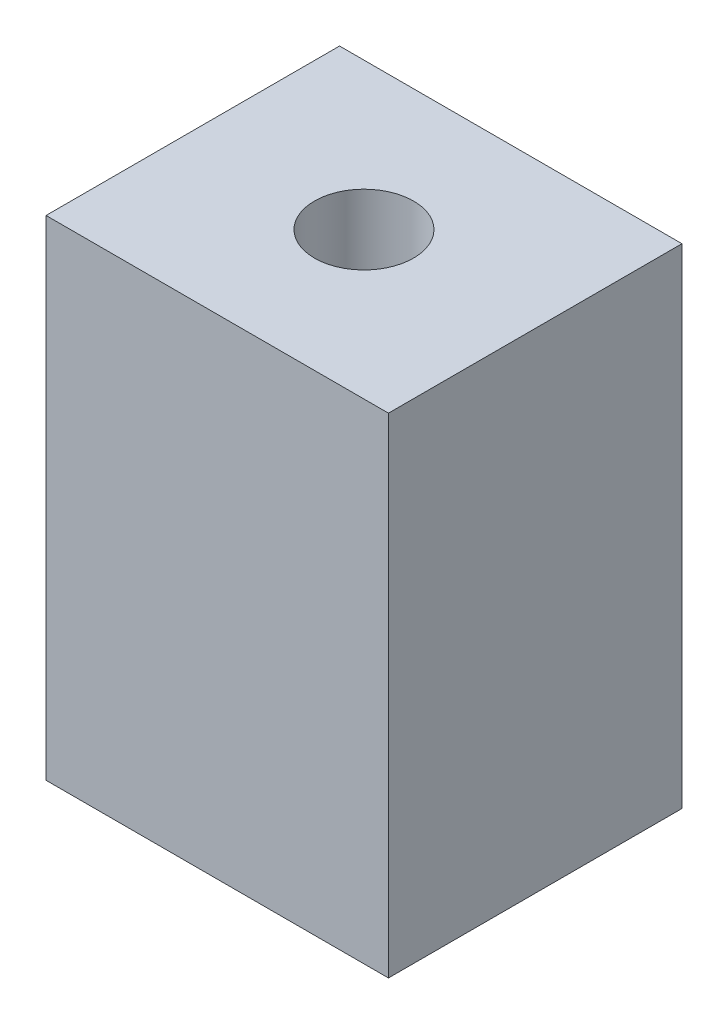
SolidWorks part; units mm, degrees
ref_plane "Front Plane" through (0, 0, 0) normal (0, 0, 1) x (1, 0, 0)
ref_plane "Top Plane" through (0, 0, 0) normal (0, 1, 0) x (1, 0, 0)
ref_plane "Right Plane" through (0, 0, 0) normal (1, 0, 0) x (0, 0, -1)
sketch "Sketch1" plane through (0, 0, 0) normal (0, 1, 0) x (1, 0, 0)
  line L1 (1.7446, -9.6481) -> (36.7446, -9.6481)
  line L2 (1.7446, -9.6481) -> (1.7446, 20.3519)
  line L3 (1.7446, 20.3519) -> (36.7446, 20.3519)
  line L4 (36.7446, -9.6481) -> (36.7446, 20.3519)
  dimension "D1" = 35
extrude "Boss-Extrude1" add sketch "Sketch1" along normal blind 50
sketch "Sketch3" plane through (0, 50, 0) normal (0, 1, 0) x (1, 0, 0)
  line L0 (36.7446, -9.6481) -> (1.7446, 20.3519) construction
  line L1 (36.7446, 20.3519) -> (1.7446, -9.6481) construction
  circle A0 centre (19.2446, 5.3519) radius 5.0607
extrude "Cut-Extrude1" cut sketch "Sketch3" against normal blind 40
